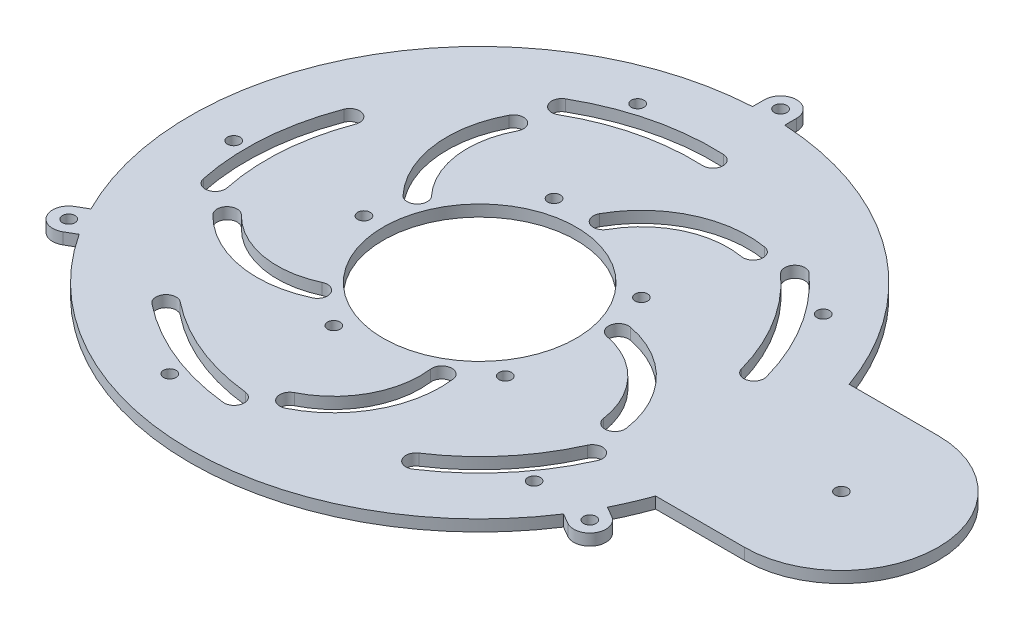
SolidWorks part; units mm, degrees
ref_plane "Front Plane" through (0, 0, 0) normal (0, 0, 1) x (1, 0, 0)
ref_plane "Top Plane" through (0, 0, 0) normal (0, 1, 0) x (1, 0, 0)
ref_plane "Right Plane" through (0, 0, 0) normal (1, 0, 0) x (0, 0, -1)
sketch "Sketch1" plane through (0, 0, 0) normal (0, 1, 0) x (1, 0, 0)
  line L0 (190.5, 50.9613) -> (143.627, 50.9613)
  line L1 (190.5, -50.9613) -> (143.627, -50.9613)
  line L2 (0, 0) -> (-60.96, 0) construction
  line L3 (0, 0) -> (-129.54, 0) construction
  line L4 (-8.4638, 158.4502) -> (-8.4638, 152.1648)
  line L5 (8.4638, 158.4502) -> (8.4638, 152.1648)
  line L6 (141.4539, -71.8952) -> (136.0105, -68.7525)
  line L7 (132.99, -86.555) -> (127.5467, -83.4123)
  line L8 (-132.99, -86.555) -> (-127.5467, -83.4123)
  line L9 (-141.4539, -71.8952) -> (-136.0105, -68.7525)
  line L10 (-117.1831, 8.9544) -> (0, 0) construction
  line L11 (0, 0) -> (-111.9293, 35.8314) construction
  arc A0 (143.627, 50.9613) -> (8.4638, 152.1648) centre (0, 0) ccw
  arc A1 (190.5, -50.9613) -> (190.5, 50.9613) centre (190.5, 0) ccw
  circle A2 centre (0, 0) radius 50.8
  circle A3 centre (-60.96, 0) radius 3.3
  circle A4 centre (-129.54, 0) radius 3.3
  circle A5 centre (-40.0301, 123.1999) radius 3.3
  circle A6 centre (-18.8377, 57.9764) radius 3.3
  circle A7 centre (104.8001, 76.1417) radius 3.3
  circle A8 centre (49.3177, 35.8314) radius 3.3
  circle A9 centre (104.8001, -76.1417) radius 3.3
  circle A10 centre (49.3177, -35.8314) radius 3.3
  circle A11 centre (-40.0301, -123.1999) radius 3.3
  circle A12 centre (-18.8377, -57.9764) radius 3.3
  circle A13 centre (0, 158.4502) radius 3.3
  arc A14 (8.4638, 158.4502) -> (-8.4638, 158.4502) centre (0, 158.4502) ccw
  circle A15 centre (137.2219, -79.2251) radius 3.3
  arc A16 (132.99, -86.555) -> (141.4539, -71.8952) centre (137.2219, -79.2251) ccw
  circle A17 centre (-137.2219, -79.2251) radius 3.3
  arc A18 (-141.4539, -71.8952) -> (-132.99, -86.555) centre (-137.2219, -79.2251) ccw
  arc A19 (-8.4638, 152.1648) -> (-136.0105, -68.7525) centre (0, 0) ccw
  arc A20 (-127.5467, -83.4123) -> (127.5467, -83.4123) centre (0, 0) ccw
  arc A21 (136.0105, -68.7525) -> (143.627, -50.9613) centre (0, 0) ccw
  circle A22 centre (190.5, 0) radius 3.3
  arc A23 (4.7039, 60.4639) -> (57.9335, 86.0601) centre (49.3177, 35.8314) cw construction
  arc A24 (58.8309, 91.2914) -> (0.0573, 63.0294) centre (49.3177, 35.8314) ccw
  arc A25 (57.0362, 80.8287) -> (9.3504, 57.8984) centre (49.3177, 35.8314) ccw
  arc A26 (57.0362, 80.8287) -> (58.8309, 91.2914) centre (57.9335, 86.0601) ccw
  arc A27 (0.0573, 63.0294) -> (9.3504, 57.8984) centre (4.7039, 60.4639) ccw
  arc A28 (58.9582, 14.2107) -> (99.7504, -28.5041) centre (49.3177, -35.8314) cw construction
  arc A29 (105.003, -27.7409) -> (59.9622, 19.4226) centre (49.3177, -35.8314) ccw
  arc A30 (94.4979, -29.2672) -> (57.9541, 8.9988) centre (49.3177, -35.8314) ccw
  arc A31 (94.4979, -29.2672) -> (105.003, -27.7409) centre (99.7504, -28.5041) ccw
  arc A32 (59.9622, 19.4226) -> (57.9541, 8.9988) centre (58.9582, 14.2107) ccw
  arc A33 (31.7343, -51.6812) -> (3.7156, -103.6765) centre (-18.8377, -57.9764) cw construction
  arc A34 (6.0645, -108.4362) -> (37.0014, -51.0256) centre (-18.8377, -57.9764) ccw
  arc A35 (1.3667, -98.9169) -> (26.4672, -52.3368) centre (-18.8377, -57.9764) ccw
  arc A36 (1.3667, -98.9169) -> (6.0645, -108.4362) centre (3.7156, -103.6765) ccw
  arc A37 (37.0014, -51.0256) -> (26.4672, -52.3368) centre (31.7343, -51.6812) ccw
  arc A38 (-39.3453, -46.1515) -> (-97.4541, -35.5716) centre (-60.96, 0) cw construction
  arc A39 (-101.2549, -39.2763) -> (-37.0941, -50.9581) centre (-60.96, 0) ccw
  arc A40 (-93.6532, -31.8668) -> (-41.5965, -41.3448) centre (-60.96, 0) ccw
  arc A41 (-93.6532, -31.8668) -> (-101.2549, -39.2763) centre (-97.4541, -35.5716) ccw
  arc A42 (-37.0941, -50.9581) -> (-41.5965, -41.3448) centre (-39.3453, -46.1515) ccw
  arc A43 (-56.051, 23.158) -> (-63.9455, 81.6921) centre (-18.8377, 57.9764) cw construction
  arc A44 (-68.6435, 84.1621) -> (-59.9268, 19.5317) centre (-18.8377, 57.9764) ccw
  arc A45 (-59.2475, 79.2221) -> (-52.1752, 26.7844) centre (-18.8377, 57.9764) ccw
  arc A46 (-59.2475, 79.2221) -> (-68.6435, 84.1621) centre (-63.9455, 81.6921) ccw
  arc A47 (-59.9268, 19.5317) -> (-52.1752, 26.7844) centre (-56.051, 23.158) ccw
  arc A48 (-109.9675, 41.4632) -> (-114.9907, -24.2733) centre (0, 0) ccw construction
  arc A49 (-114.934, 43.3358) -> (-120.184, -25.3695) centre (0, 0) ccw
  arc A50 (-105.0011, 39.5907) -> (-109.7974, -23.177) centre (0, 0) ccw
  arc A51 (-105.0011, 39.5907) -> (-114.934, 43.3358) centre (-109.9675, 41.4632) ccw
  arc A52 (-120.184, -25.3695) -> (-109.7974, -23.177) centre (-114.9907, -24.2733) ccw
  arc A53 (5.452, 117.3982) -> (-58.6194, 101.8618) centre (0, 0) ccw construction
  arc A54 (5.6983, 122.7002) -> (-61.2668, 106.4622) centre (0, 0) ccw
  arc A55 (5.2058, 112.0962) -> (-55.972, 97.2615) centre (0, 0) ccw
  arc A56 (5.2058, 112.0962) -> (5.6983, 122.7002) centre (5.452, 117.3982) ccw
  arc A57 (-61.2668, 106.4622) -> (-55.972, 97.2615) centre (-58.6194, 101.8618) ccw
  arc A58 (113.3371, 31.0928) -> (78.762, 87.2274) centre (0, 0) ccw construction
  arc A59 (118.4557, 32.4971) -> (82.3191, 91.1668) centre (0, 0) ccw
  arc A60 (108.2185, 29.6886) -> (75.2049, 83.2879) centre (0, 0) ccw
  arc A61 (108.2185, 29.6886) -> (118.4557, 32.4971) centre (113.3371, 31.0928) ccw
  arc A62 (82.3191, 91.1668) -> (75.2049, 83.2879) centre (78.762, 87.2274) ccw
  arc A63 (64.5941, -98.1818) -> (107.2969, -47.9523) centre (0, 0) ccw construction
  arc A64 (67.5114, -102.6159) -> (112.1427, -50.118) centre (0, 0) ccw
  arc A65 (61.6769, -93.7476) -> (102.4511, -45.7867) centre (0, 0) ccw
  arc A66 (61.6769, -93.7476) -> (67.5114, -102.6159) centre (64.5941, -98.1818) ccw
  arc A67 (112.1427, -50.118) -> (102.4511, -45.7867) centre (107.2969, -47.9523) ccw
  arc A68 (-73.4157, -91.7725) -> (-12.4488, -116.8635) centre (0, 0) ccw construction
  arc A69 (-76.7314, -95.9172) -> (-13.011, -122.1414) centre (0, 0) ccw
  arc A70 (-70.1001, -87.6278) -> (-11.8866, -111.5857) centre (0, 0) ccw
  arc A71 (-70.1001, -87.6278) -> (-76.7314, -95.9172) centre (-73.4157, -91.7725) ccw
  arc A72 (-13.011, -122.1414) -> (-11.8866, -111.5857) centre (-12.4488, -116.8635) ccw
  point P32 (0, 0)
  point P38 (27.2325, 81.7596)
  point P53 (0, 0)
  point P61 (86.1733, -0.6346)
  point P69 (26.0255, -82.1518)
  point P77 (-70.0887, -50.138)
  point P85 (-69.3427, 51.1648)
  point P90 (0, 0)
  point P91 (-117.1831, 8.9544)
  point P103 (-27.6954, 114.2148)
  point P110 (100.0664, 61.6342)
  point P117 (89.5398, -76.1228)
  point P124 (-44.7277, -108.6807)
  point P129 (0, 0)
  dimension "D1" = 5
  dimension "D2" = 3
  dimension "D3" = 190.5
  dimension "D4" = 5
  dimension "D5" = 129.54
extrude "Boss-Extrude1" add sketch "Sketch1" along normal blind 6 contours A1 A0 A12 A11 A10 A9 A8 A7 A6 A5 A4 A3 A2
